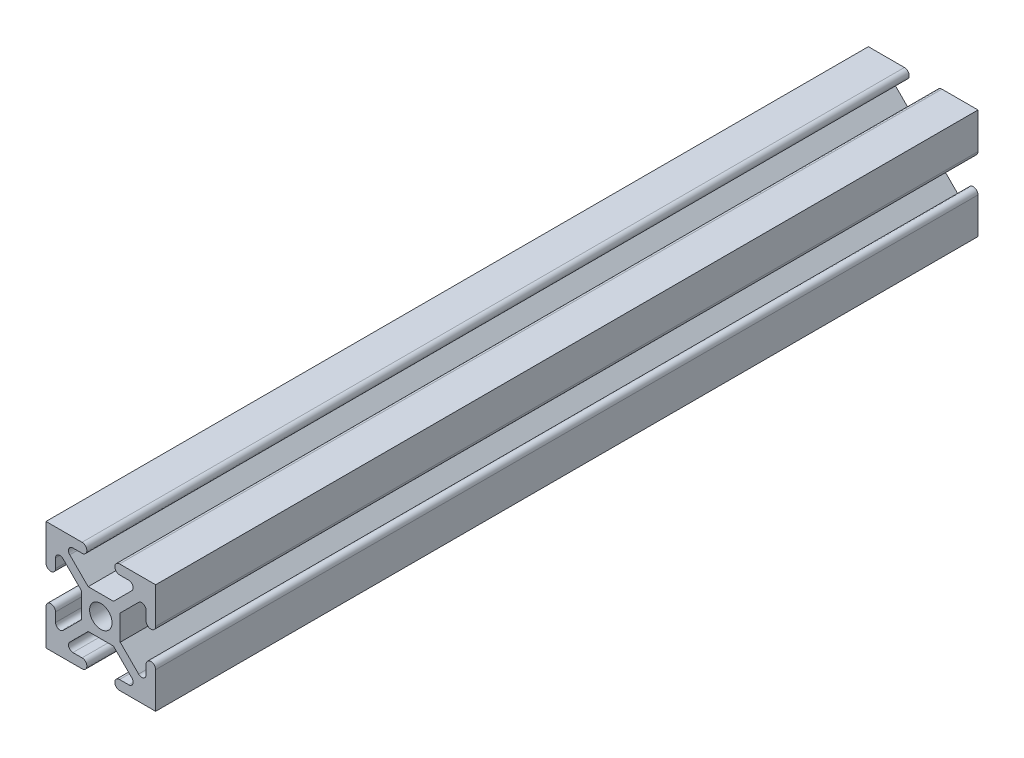
SolidWorks part; units mm, degrees
ref_plane "Front Plane" through (0, 0, 0) normal (0, 0, 1) x (1, 0, 0)
ref_plane "Top Plane" through (0, 0, 0) normal (0, 1, 0) x (1, 0, 0)
ref_plane "Right Plane" through (0, 0, 0) normal (1, 0, 0) x (0, 0, -1)
sketch "Sketch1" plane through (0, 0, 0) normal (0, 0, 1) x (1, 0, 0)
  line L2 (-12.7, -12.7) -> (-4.3434, -12.7)
  line L3 (-4.3434, -10.4902) -> (-6.4748, -10.4902)
  line L4 (-7.1932, -8.7558) -> (-2.9332, -4.4958)
  line L5 (-2.9332, -4.4958) -> (2.9332, -4.4958)
  line L6 (2.9332, -4.4958) -> (7.1932, -8.7558)
  line L7 (6.4748, -10.4902) -> (4.3434, -10.4902)
  line L8 (4.3434, -12.7) -> (12.7, -12.7)
  line L11 (12.7, -12.7) -> (12.7, -4.3434)
  line L12 (10.4902, -4.3434) -> (10.4902, -6.4748)
  line L13 (8.7558, -7.1932) -> (4.4958, -2.9332)
  line L14 (4.4958, -2.9332) -> (4.4958, 2.9332)
  line L15 (4.4958, 2.9332) -> (8.7558, 7.1932)
  line L16 (10.4902, 6.4748) -> (10.4902, 4.3434)
  line L17 (12.7, 4.3434) -> (12.7, 12.7)
  line L20 (12.7, 12.7) -> (4.3434, 12.7)
  line L21 (4.3434, 10.4902) -> (6.4748, 10.4902)
  line L22 (7.1932, 8.7558) -> (2.9332, 4.4958)
  line L23 (2.9332, 4.4958) -> (-2.9332, 4.4958)
  line L24 (-2.9332, 4.4958) -> (-7.1932, 8.7558)
  line L25 (-6.4748, 10.4902) -> (-4.3434, 10.4902)
  line L26 (-4.3434, 12.7) -> (-12.7, 12.7)
  line L29 (-12.7, 12.7) -> (-12.7, 4.3434)
  line L30 (-10.4902, 4.3434) -> (-10.4902, 6.4748)
  line L31 (-8.7558, 7.1932) -> (-4.4958, 2.9332)
  line L32 (-4.4958, 2.9332) -> (-4.4958, -2.9332)
  line L33 (-4.4958, -2.9332) -> (-8.7558, -7.1932)
  line L34 (-10.4902, -6.4748) -> (-10.4902, -4.3434)
  line L35 (-12.7, -4.3434) -> (-12.7, -12.7)
  circle A0 centre (0, 0) radius 2.6035
  arc A6 (-4.3434, -12.7) -> (-4.3434, -10.4902) centre (-4.3434, -11.5951) ccw
  arc A7 (-6.4748, -10.4902) -> (-7.1932, -8.7558) centre (-6.4748, -9.4742) cw
  arc A10 (7.1932, -8.7558) -> (6.4748, -10.4902) centre (6.4748, -9.4742) cw
  arc A11 (4.3434, -10.4902) -> (4.3434, -12.7) centre (4.3434, -11.5951) ccw
  arc A17 (12.7, -4.3434) -> (10.4902, -4.3434) centre (11.5951, -4.3434) ccw
  arc A18 (10.4902, -6.4748) -> (8.7558, -7.1932) centre (9.4742, -6.4748) cw
  arc A21 (8.7558, 7.1932) -> (10.4902, 6.4748) centre (9.4742, 6.4748) cw
  arc A22 (10.4902, 4.3434) -> (12.7, 4.3434) centre (11.5951, 4.3434) ccw
  arc A28 (4.3434, 12.7) -> (4.3434, 10.4902) centre (4.3434, 11.5951) ccw
  arc A29 (6.4748, 10.4902) -> (7.1932, 8.7558) centre (6.4748, 9.4742) cw
  arc A32 (-7.1932, 8.7558) -> (-6.4748, 10.4902) centre (-6.4748, 9.4742) cw
  arc A33 (-4.3434, 10.4902) -> (-4.3434, 12.7) centre (-4.3434, 11.5951) ccw
  arc A39 (-12.7, 4.3434) -> (-10.4902, 4.3434) centre (-11.5951, 4.3434) ccw
  arc A40 (-10.4902, 6.4748) -> (-8.7558, 7.1932) centre (-9.4742, 6.4748) cw
  arc A43 (-8.7558, -7.1932) -> (-10.4902, -6.4748) centre (-9.4742, -6.4748) cw
  arc A44 (-10.4902, -4.3434) -> (-12.7, -4.3434) centre (-11.5951, -4.3434) ccw
  point P101 (-4.4958, 0)
  point P102 (0, 4.4958)
  point P103 (4.4958, 0)
  point P127 (0, -4.4958)
extrude "Boss-Extrude1" add sketch "Sketch1" against normal blind 190.5
